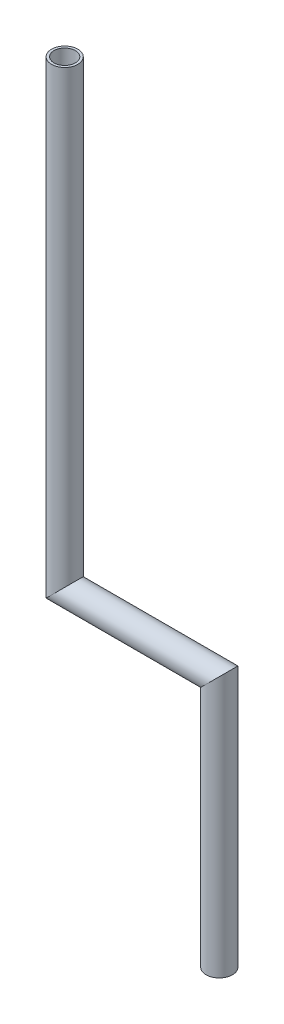
SolidWorks part; units mm, degrees
ref_plane "Front Plane" through (0, 0, 0) normal (0, 0, 1) x (1, 0, 0)
ref_plane "Top Plane" through (0, 0, 0) normal (0, 1, 0) x (1, 0, 0)
ref_plane "Right Plane" through (0, 0, 0) normal (1, 0, 0) x (0, 0, -1)
sketch "Sketch1" plane through (0, 0, 0) normal (0, 0, 1) x (1, 0, 0)
  line L0 (0, 0) -> (100.9485, 0)
  line L1 (0, 0) -> (0, 300)
  line L2 (100.9485, 0) -> (100.9485, -164.2791)
ref_plane "Plane1" through (0, 300, 0) normal (0, 1, 0) x (1, 0, 0)
sketch "Sketch2" plane through (0, 300, 0) normal (0, 1, 0) x (1, 0, 0)
  circle A0 centre (0, 0) radius 8.5903
  circle A1 centre (0, 0) radius 6.9838
sweep "Sweep1" add profiles "Sketch2" path "Sketch1"
